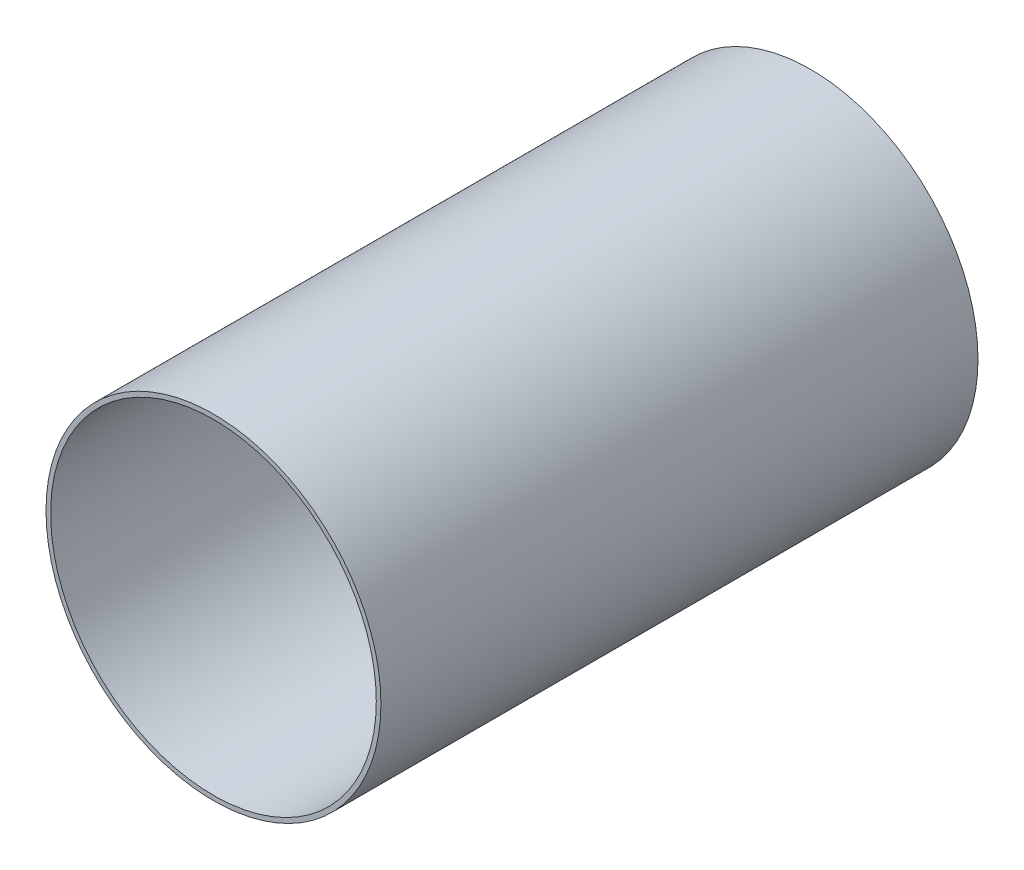
SolidWorks part; units mm, degrees
ref_plane "Plan de face" through (0, 0, 0) normal (0, 0, 1) x (1, 0, 0)
ref_plane "Plan de dessus" through (0, 0, 0) normal (0, 1, 0) x (1, 0, 0)
ref_plane "Plan de droite" through (0, 0, 0) normal (1, 0, 0) x (0, 0, -1)
sketch "Esquisse2" plane through (0, 0, 0) normal (0, 0, 1) x (1, 0, 0)
  circle A0 centre (0, 0) radius 78.359
  circle A1 centre (0, 0) radius 76.2
  dimension "D1" = 156.718
  dimension "D2" = 152.4
extrude "Boss.-Extru.1" add sketch "Esquisse2" along normal blind 279.4
